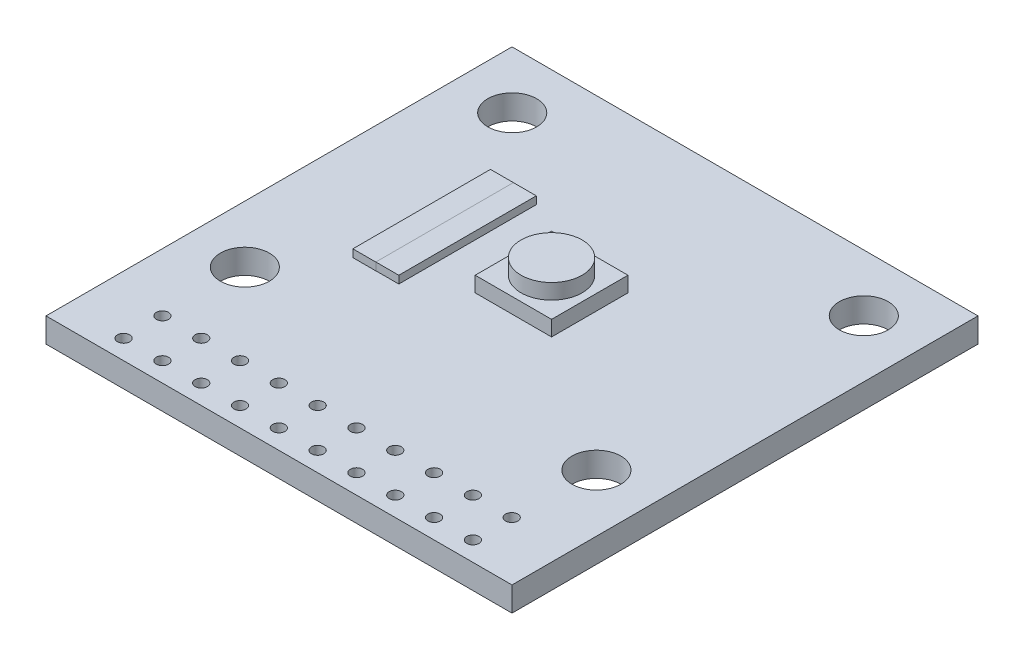
SolidWorks part; units mm, degrees
ref_plane "Alzado" through (0, 0, 0) normal (0, 0, 1) x (1, 0, 0)
ref_plane "Planta" through (0, 0, 0) normal (0, 1, 0) x (1, 0, 0)
ref_plane "Vista lateral" through (0, 0, 0) normal (1, 0, 0) x (0, 0, -1)
sketch "Croquis1" plane through (0, 0, 0) normal (0, 1, 0) x (1, 0, 0)
  line L1 (-15.25, -15.25) -> (15.25, -15.25)
  line L2 (-15.25, -15.25) -> (-15.25, 15.25)
  line L3 (-15.25, 15.25) -> (15.25, 15.25)
  line L4 (15.25, -15.25) -> (15.25, 15.25)
  line L5 (-15.25, -15.25) -> (15.25, 15.25) construction
  line L6 (-15.25, 15.25) -> (15.25, -15.25) construction
  point P0 (0, 0)
  dimension "D1" = 30.5
  dimension "D2" = 30.5
extrude "Saliente-Extruir1" add sketch "Croquis1" along normal blind 1.6
sketch "Croquis2" plane through (0, 1.6, 0) normal (0, 1, 0) x (1, 0, 0)
  line L0 (0, 0) -> (0, 25.1156) construction
  circle A0 centre (-11.505, 11.52) radius 1.6
  circle A1 centre (11.505, 11.52) radius 1.6
  circle A2 centre (11.505, -5.98) radius 1.6
  circle A3 centre (-11.505, -5.98) radius 1.6
  dimension "D1" = 3.73
  dimension "D2" = 3.2
  dimension "D4" = 3.2
  dimension "D6" = 3.2
  dimension "D3" = 23.01
  dimension "D5" = 17.5
extrude "Cortar-Extruir3" cut sketch "Croquis2" against normal through all
sketch "Croquis3" plane through (0, 1.6, 0) normal (0, 1, 0) x (1, 0, 0)
  line L0 (-15.9747, -12.6506) -> (16.6004, -12.6506) construction
  circle A0 centre (-11.44, -13.98) radius 0.4
  circle A1 centre (-8.9, -13.98) radius 0.4
  circle A2 centre (-6.36, -13.98) radius 0.4
  circle A3 centre (-3.82, -13.98) radius 0.4
  circle A4 centre (-1.28, -13.98) radius 0.4
  circle A5 centre (1.26, -13.98) radius 0.4
  circle A6 centre (3.8, -13.98) radius 0.4
  circle A7 centre (6.34, -13.98) radius 0.4
  circle A8 centre (8.88, -13.98) radius 0.4
  circle A9 centre (11.42, -13.98) radius 0.4
  circle A10 centre (-11.44, -11.44) radius 0.4
  circle A11 centre (-8.9, -11.44) radius 0.4
  circle A12 centre (-6.36, -11.44) radius 0.4
  circle A13 centre (-3.82, -11.44) radius 0.4
  circle A14 centre (-1.28, -11.44) radius 0.4
  circle A15 centre (1.26, -11.44) radius 0.4
  circle A16 centre (3.8, -11.44) radius 0.4
  circle A17 centre (6.34, -11.44) radius 0.4
  circle A18 centre (8.88, -11.44) radius 0.4
  circle A19 centre (11.42, -11.44) radius 0.4
  dimension "D1" = 0.8
  dimension "D5" = 0.8
  dimension "D2" = 1.27
  dimension "D3" = 3.81
  dimension "D6" = 2.54
  dimension "D4" = 10
  dimension "D7" = 10
extrude "Cortar-Extruir4" cut sketch "Croquis3" against normal through all
sketch "Croquis4" plane through (0, 1.6, 0) normal (0, 1, 0) x (1, 0, 0)
  line L0 (-2.51, 2.6) -> (2.49, 2.6) construction
  line L1 (-2.51, 0.1) -> (2.49, 0.1)
  line L2 (-2.51, 0.1) -> (-2.51, 5.1)
  line L3 (-2.51, 5.1) -> (2.49, 5.1)
  line L4 (2.49, 0.1) -> (2.49, 5.1)
  line L5 (-0.01, 0.1) -> (-0.01, 5.1) construction
  line L6 (15.25, 15.25) -> (-15.25, 15.25) construction
  line L7 (-15.25, 15.25) -> (-15.25, -15.25) construction
  point P8 (-0.01, 2.6)
  dimension "D1" = 5
  dimension "D2" = 5
  dimension "D3" = 12.65
  dimension "D4" = 15.24
extrude "Saliente-Extruir2" add sketch "Croquis4" along normal blind 1
sketch "Croquis5" plane through (0, 2.6, 0) normal (0, 1, 0) x (1, 0, 0)
  circle A0 centre (-0.01, 2.6) radius 2
extrude "Saliente-Extruir3" add sketch "Croquis5" along normal blind 1
sketch "Croquis6" plane through (0, 1.6, 0) normal (0, 1, 0) x (1, 0, 0)
  line L0 (-2.51, 5.1) -> (-2.51, 0.1) construction
  line L1 (-7.01, 7.1) -> (-5.51, 7.1)
  line L2 (-7.01, 7.1) -> (-7.01, -1.9)
  line L3 (-7.01, -1.9) -> (-5.51, -1.9)
  line L4 (-5.51, 7.1) -> (-5.51, -1.9)
  point P4 (-5.51, 2.6)
  point P7 (-2.51, 2.6)
  dimension "D1" = 1.5
  dimension "D2" = 9
  dimension "D3" = 3
extrude "Saliente-Extruir4" add sketch "Croquis6" along normal blind 0.5
sketch "Croquis7" plane through (0, 1.6, 0) normal (0, 1, 0) x (1, 0, 0)
  line L1 (-7.01, 7.1) -> (-8.51, 7.1)
  line L2 (-7.01, 7.1) -> (-7.01, -1.9056)
  line L3 (-7.01, -1.9056) -> (-8.51, -1.9056)
  line L4 (-8.51, 7.1) -> (-8.51, -1.9056)
  dimension "D1" = 1.5
extrude "Saliente-Extruir6" add sketch "Croquis7" along normal blind 0.5 separate body
